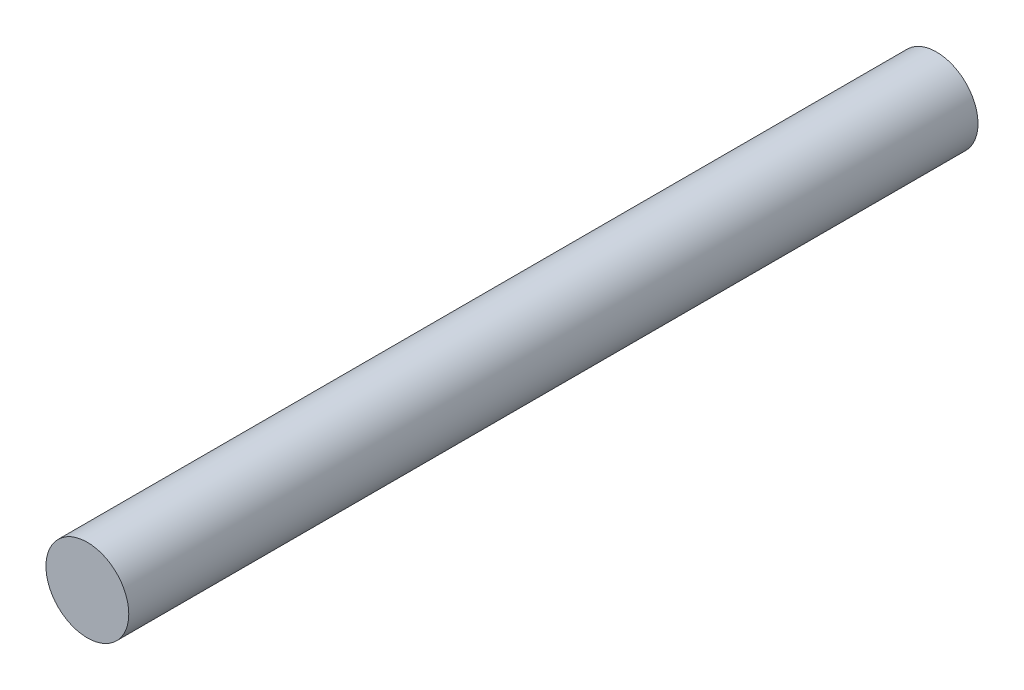
SolidWorks part; units mm, degrees
material "AISI 304"
ref_plane "Front Plane" through (0, 0, 0) normal (0, 0, 1) x (1, 0, 0)
ref_plane "Top Plane" through (0, 0, 0) normal (0, 1, 0) x (1, 0, 0)
ref_plane "Right Plane" through (0, 0, 0) normal (1, 0, 0) x (0, 0, -1)
sketch "Sketch1" plane through (0, 0, 0) normal (0, 0, 1) x (1, 0, 0)
  circle A0 centre (0, 0) radius 4
  dimension "D1" = 8
extrude "Boss-Extrude1" add sketch "Sketch1" along normal blind 82
equation "\"Base-Width\"= 420"
equation "\"Base-Height\"= 320"
equation "\"Support-Rod-Diameter\"= 16"
equation "\"Support-Rod-X-Offset\"= 35"
equation "\"Support-Rod-Y-Offset\"= 35"
equation "\"Base-Thickness\"= 5"
equation "\"Base-Depth\"= 82"
equation "\"Corner-Radius-Major\"= \"Support-Rod-Diameter\""
equation "\"Cutout-Horizontal\"= \"Base-Width\" * 0.8"
equation "\"Cutout-Vertical\"= \"Base-Height\" * 0.6"
equation "\"Outer-Support-Bore-Diameter\"= 6.1"
equation "\"Inner-Support-Bore-Diameter\"= 8.2"
equation "\"Cutout-Depth\"= 20"
equation "\"D1@Boss-Extrude1\"=\"Base-Depth\""
equation "\"D2@Sketch1\"=\"Base-Width\""
equation "\"D1@Sketch7\"=\"Cutout-Vertical\""
equation "\"D2@Sketch6\"=\"Cutout-Horizontal\""
equation "\"D2@Sketch8\"= \"Base-Width\" - ( \"Support-Rod-X-Offset\" ) + 5"
equation "\"D1@Sketch8\" = \"Base-Height\" - \"Support-Rod-Y-Offset\" + 10"
equation "\"D1@Major-Fillet\" = \"Corner-Radius-Major\""
equation "\"D1@Sketch1\"=\"Base-Height\""
